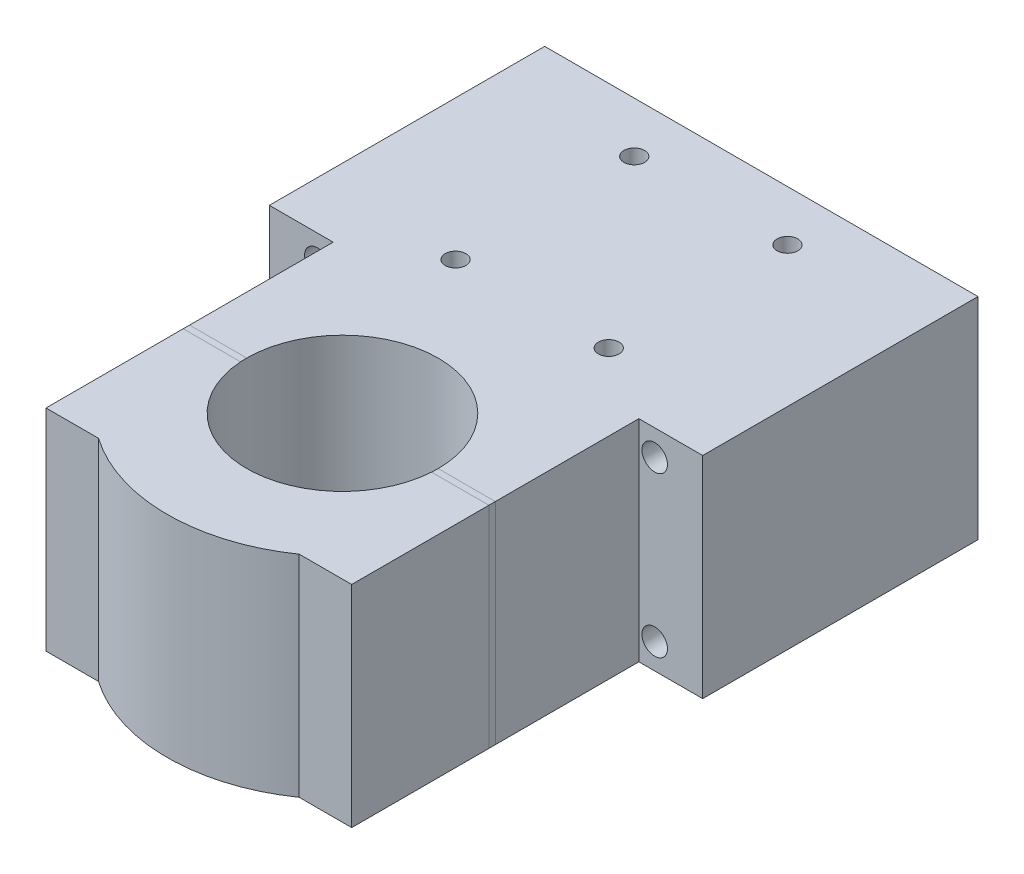
SolidWorks part; units mm, degrees
ref_plane "Front Plane" through (0, 0, 0) normal (0, 0, 1) x (1, 0, 0)
ref_plane "Top Plane" through (0, 0, 0) normal (0, 1, 0) x (1, 0, 0)
ref_plane "Right Plane" through (0, 0, 0) normal (1, 0, 0) x (0, 0, -1)
sketch "Sketch1" plane through (0, 0, 0) normal (0, 1, 0) x (1, 0, 0)
  line L0 (-47.3083, 17.816) -> (20.5912, 17.816)
  line L1 (20.5912, 17.816) -> (20.5912, 9.6753)
  line L2 (-47.3083, 17.816) -> (-47.3083, 9.6753)
  line L3 (-47.3083, 9.6753) -> (-37.3083, 9.6753)
  line L4 (10.5912, 9.6753) -> (20.5912, 9.6753)
  line L5 (-37.3083, 9.6753) -> (-37.3083, -35.3247)
  line L6 (10.5912, 9.6753) -> (10.5912, -35.3247)
  line L10 (-37.3083, -35.3247) -> (-29.0824, -35.3247)
  line L11 (10.5912, -35.3247) -> (2.3653, -35.3247)
  circle A0 centre (-13.3585, -12.8247) radius 15
  arc A1 (-29.0824, -35.3247) -> (2.3653, -35.3247) centre (-13.3585, -12.8247) ccw
  dimension "D1" = 45
  dimension "D2" = 45
  dimension "D5" = 10
  dimension "D6" = 10
  dimension "D7" = 67.8995
extrude "Boss-Extrude3" add sketch "Sketch1" along normal blind 33 contours A0 | L5 L10 A1 L11 L6 L4 L1 L0 L2 L3
sketch "Sketch8" plane through (-37.3083, 0, 0) normal (-1, 0, 0) x (0, 0, 1)
  line L0 (12.8247, 33) -> (12.8247, 0)
  line L1 (-9.6753, 33) -> (35.3247, 33) construction
  line L2 (-9.6753, 0) -> (35.3247, 0) construction
  line L3 (13.8247, 33) -> (13.8247, 0)
  dimension "D1" = 1
split line "Split Line1"
sketch "Sketch10" plane through (0, 33, 0) normal (0, 1, 0) x (1, 0, 0)
  line L0 (-37.3083, -12.8247) -> (-28.3585, -12.8247)
  line L1 (1.6415, -12.8247) -> (10.5912, -12.8247)
  line L2 (10.5912, 9.6753) -> (10.5912, -35.3247) construction
  line L3 (-37.3083, -13.8247) -> (-28.3252, -13.8247)
  line L4 (10.5912, -13.8247) -> (1.6081, -13.8247)
  circle A0 centre (-13.3585, -12.8247) radius 15 construction
split line "Split Line2"
sketch "Sketch11" plane through (10.5912, 0, 0) normal (1, 0, 0) x (0, 0, -1)
  line L0 (-12.8247, 33) -> (-12.8247, 0)
  line L1 (9.6753, 0) -> (-35.3247, 0) construction
  line L2 (-13.8247, 33) -> (-13.8247, 0)
split line "Split Line3"
sketch "Sketch12" plane through (0, 0, -17.816) normal (0, 0, -1) x (-1, 0, 0)
  line L0 (47.3083, 0) -> (-20.5912, 0) construction
  line L1 (47.3083, 33) -> (47.3083, 0) construction
  line L3 (47.3083, 33) -> (-20.5912, 33) construction
  line L4 (-20.5912, 33) -> (-20.5912, 0) construction
  circle A0 centre (39.7883, 4) radius 2
  circle A1 centre (39.7883, 29) radius 2
  circle A2 centre (-13.0712, 29) radius 2
  circle A3 centre (-13.0712, 4) radius 2
  dimension "D1" = 4
  dimension "D2" = 7.52
  dimension "D3" = 7.52
  dimension "D4" = 4
  dimension "D5" = 7.52
  dimension "D6" = 7.52
  dimension "D7" = 4
extrude "Cut-Extrude1" cut sketch "Sketch12" against normal blind 10
sketch "Sketch13" plane through (0, 33, 0) normal (0, 1, 0) x (1, 0, 0)
  line L0 (20.5912, 17.816) -> (20.5912, 9.6753) construction
  line L1 (-47.3083, 17.816) -> (20.5912, 17.816)
  line L2 (-47.3083, 17.816) -> (-47.3083, 52.816)
  line L3 (-47.3083, 52.816) -> (20.5912, 52.816)
  line L4 (20.5912, 17.816) -> (20.5912, 52.816)
  dimension "D1" = 0
  dimension "D2" = 35
extrude "Boss-Extrude4" add sketch "Sketch13" against normal blind 33
sketch "Sketch14" plane through (0, 33, 0) normal (0, 1, 0) x (1, 0, 0)
  line L3 (-47.3083, 52.816) -> (-47.3083, 9.6753) construction
  circle A0 centre (-25.3583, 16.9) radius 1.62
  circle A1 centre (-1.3583, 16.9) radius 1.62
  circle A2 centre (-25.3583, 44.9) radius 1.62
  circle A3 centre (-1.3583, 44.9) radius 1.62
  dimension "D4" = 21.95
  dimension "D5" = 3.24
  dimension "D6" = 3.24
  dimension "D7" = 3.24
  dimension "D8" = 3.24
  dimension "D1" = 28
  dimension "D2" = 28
  dimension "D3" = 24
extrude "Cut-Extrude2" cut sketch "Sketch14" against normal blind 10
